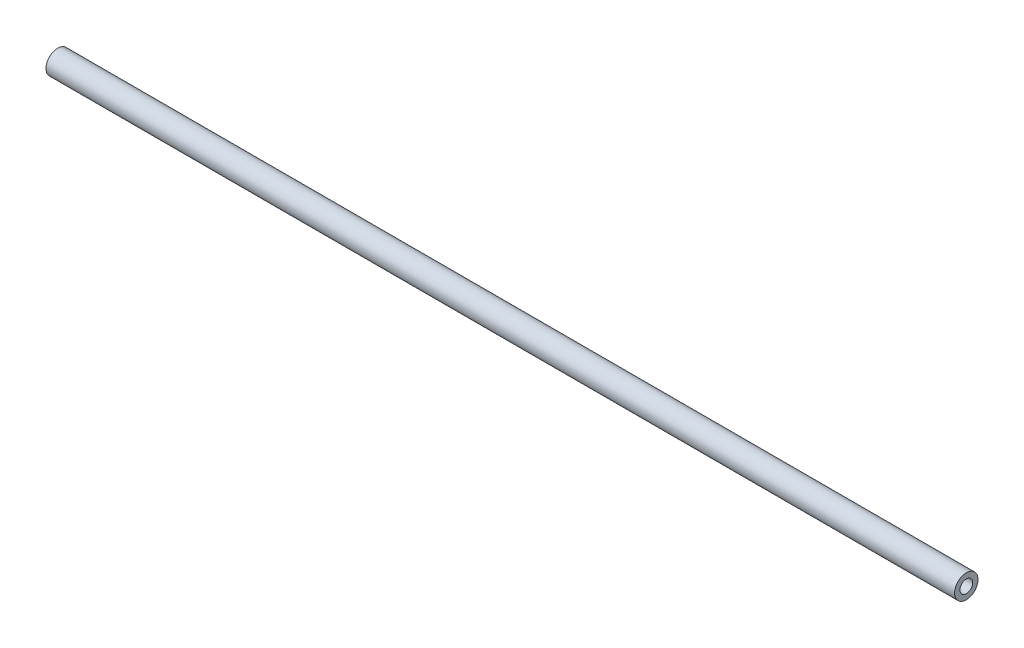
SolidWorks part; units mm, degrees
material "Plain Carbon Steel"
ref_plane "Front Plane" through (0, 0, 0) normal (0, 0, 1) x (1, 0, 0)
ref_plane "Top Plane" through (0, 0, 0) normal (0, 1, 0) x (1, 0, 0)
ref_plane "Right Plane" through (0, 0, 0) normal (1, 0, 0) x (0, 0, -1)
sketch "Sketch1" plane through (0, 0, 0) normal (1, 0, 0) x (0, 0, -1)
  circle A0 centre (0, 0) radius 3.175
  dimension "D1" = 6.35
extrude "Boss-Extrude1" add sketch "Sketch1" along normal mid plane 246.38
hole_wizard "Tap Drill for #8-32 Tap1" positions "Sketch2" profile "Sketch4" hole size "#8-32" standard "ANSI Inch"
sketch "Sketch2" plane through (123.19, 0, 0) normal (1, 0, 0) x (0, 0, -1)
  point P0 (0, 0)
sketch "Sketch4" plane through (123.19, 0, 0) normal (0, 1, 0) x (0, 0, -1)
  line L0 (0, 0) -> (0, 11.1978)
  line L1 (0, 11.1978) -> (1.7272, 10.16)
  line L2 (1.7272, 10.16) -> (1.7272, 0)
  line L5 (1.7272, 0) -> (0, 0)
  line L10 (0, 11.1978) -> (-1.7272, 10.16) construction
  line L11 (0, -6.35) -> (0, 107.95) construction
  dimension "Hole Dia." = 3.4544
  dimension "Hole Depth" = 10.16
  dimension "Drill Angle" = 118
mirror "Mirror1" about plane through (0, 0, 0) normal (1, 0, 0) of "Tap Drill for #8-32 Tap1"
